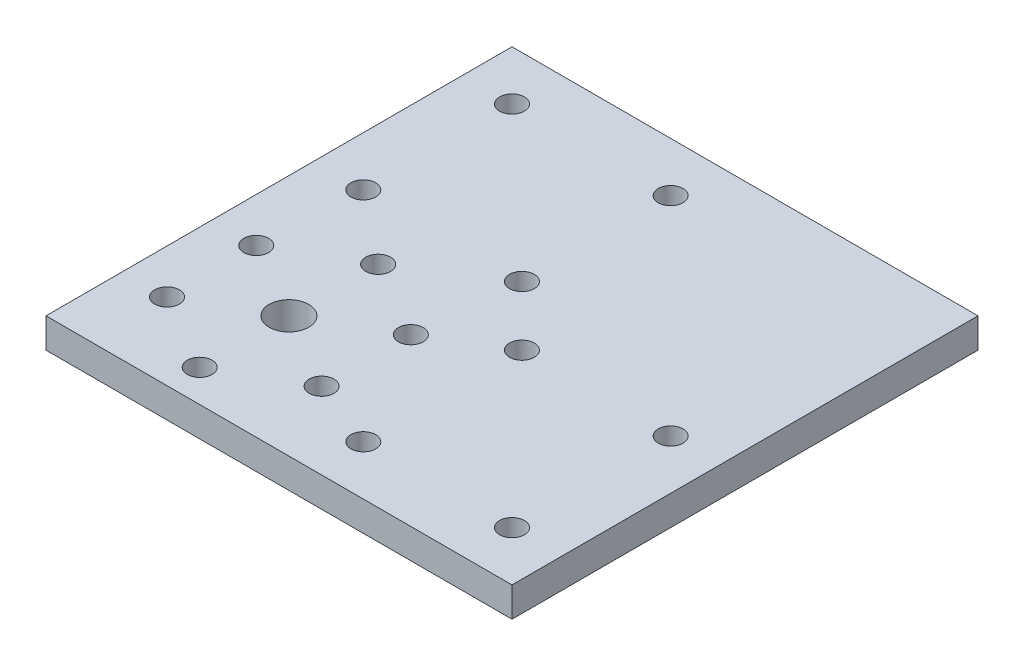
SolidWorks part; units mm, degrees
ref_plane "Front Plane" through (0, 0, 0) normal (0, 0, 1) x (1, 0, 0)
ref_plane "Top Plane" through (0, 0, 0) normal (0, 1, 0) x (1, 0, 0)
ref_plane "Right Plane" through (0, 0, 0) normal (1, 0, 0) x (0, 0, -1)
sketch "Sketch1" plane through (0, 0, 0) normal (0, 1, 0) x (1, 0, 0)
  line L0 (8, -10.5) -> (14, -10.5) construction
  line L1 (8, -7.5) -> (-8, -7.5) construction
  line L2 (8, -7.5) -> (8, 7.5) construction
  line L3 (8, 7.5) -> (-8, 7.5) construction
  line L4 (-8, -7.5) -> (-8, 7.5) construction
  line L5 (8, -7.5) -> (-8, 7.5) construction
  line L6 (8, 7.5) -> (-8, -7.5) construction
  line L7 (29, -29.5) -> (14, -29.5) construction
  line L8 (29, -29.5) -> (29, -13.5) construction
  line L9 (29, -13.5) -> (14, -13.5) construction
  line L10 (14, -29.5) -> (14, -13.5) construction
  line L11 (29, -29.5) -> (14, -13.5) construction
  line L12 (29, -13.5) -> (14, -29.5) construction
  line L13 (-13, 12.5) -> (34, 12.5)
  line L14 (34, 12.5) -> (34, -34.5)
  line L15 (34, -34.5) -> (-13, -34.5)
  line L16 (-13, -34.5) -> (-13, 12.5)
  line L17 (11, -7.5) -> (11, -13.5) construction
  circle A0 centre (8, -7.5) radius 3 construction
  circle A1 centre (14, -13.5) radius 3 construction
  point P0 (0, 0)
  point P6 (21.5, -21.5)
  dimension "D3" = 6
  dimension "D1" = 15
  dimension "D2" = 16
  dimension "D5" = 5
  dimension "D6" = 5
  dimension "D7" = 5
  dimension "D8" = 5
extrude "Boss-Extrude1" add sketch "Sketch1" along normal blind 3
hole_wizard "Tap Drill for M3x0.5 Tap1" positions "Sketch2" profile "Sketch3" hole size "M3x0.5" standard "ANSI Metric" end condition through all
sketch "Sketch2" plane through (0, 3, 0) normal (0, 1, 0) x (1, 0, 0)
  point P0 (-8, 7.5)
  point P3 (8, 7.5)
  point P6 (8, -7.5)
  point P9 (-8, -7.5)
  point P12 (14, -13.5)
  point P15 (29, -13.5)
  point P18 (29, -29.5)
  point P21 (14, -29.5)
sketch "Sketch3" plane through (-8, 3, -7.5) normal (1, 0, 0) x (0, 0, 1)
  line L0 (0, 0) -> (0, 3)
  line L1 (0, 3) -> (1.25, 3)
  line L2 (1.25, 3) -> (1.25, 0)
  line L5 (1.25, 0) -> (0, 0)
  line L11 (0, -6.35) -> (0, 107.95) construction
  dimension "Thru Hole Dia." = 2.5
  dimension "Thru Hole Depth" = 3
sketch "Chube Mounting" plane through (0, 3, 0) normal (0, 1, 0) x (1, 0, 0)
  line L1 (11.5, -10) -> (-13, -10) construction
  line L2 (11.5, -10) -> (11.5, -34.5) construction
  line L3 (11.5, -34.5) -> (-13, -34.5) construction
  line L4 (-13, -10) -> (-13, -34.5) construction
  line L5 (11.5, -10) -> (-13, -34.5) construction
  line L6 (11.5, -34.5) -> (-13, -10) construction
  circle A0 centre (-0.75, -22.25) radius 9 construction
  point P0 (-0.75, -22.25)
  point P6 (-0.75, -13.25)
  point P10 (7.0442, -17.75)
  point P13 (7.0442, -26.75)
  point P14 (-0.75, -31.25)
  point P15 (-8.5442, -26.75)
  point P16 (-8.5442, -17.75)
  point P17 (-0.75, -22.25)
  dimension "D2" = 18
  dimension "D1" = 10
  dimension "D3" = 6
hole_wizard "Tap Drill for M3x0.5 Tap2" positions "Sketch5" profile "Sketch6" hole size "M3x0.5" standard "ANSI Metric" end condition through all
sketch "Sketch5" plane through (0, 3, 0) normal (0, 1, 0) x (1, 0, 0)
  point P0 (-0.75, -13.25)
  point P3 (-8.5442, -17.75)
  point P6 (-8.5442, -26.75)
  point P9 (-0.75, -31.25)
  point P12 (7.0442, -26.75)
  point P15 (7.0442, -17.75)
sketch "Sketch6" plane through (-0.75, 3, 13.25) normal (1, 0, 0) x (0, 0, 1)
  line L0 (0, 0) -> (0, 3)
  line L1 (0, 3) -> (1.25, 3)
  line L2 (1.25, 3) -> (1.25, 0)
  line L5 (1.25, 0) -> (0, 0)
  line L11 (0, -6.35) -> (0, 107.95) construction
  dimension "Thru Hole Dia." = 2.5
  dimension "Thru Hole Depth" = 3
hole_wizard "Ø4.0 (4) Diameter Hole1" positions "Sketch7" profile "Sketch8" hole size "Ø4.0" standard "ANSI Metric" end condition through all
sketch "Sketch7" plane through (0, 3, 0) normal (0, 1, 0) x (1, 0, 0)
  point P0 (-0.75, -22.25)
sketch "Sketch8" plane through (-0.75, 3, 22.25) normal (1, 0, 0) x (0, 0, 1)
  line L0 (0, 0) -> (0, 3)
  line L1 (0, 3) -> (2, 3)
  line L2 (2, 3) -> (2, 0)
  line L5 (2, 0) -> (0, 0)
  line L11 (0, -6.35) -> (0, 107.95) construction
  dimension "Thru Hole Dia." = 4
  dimension "Thru Hole Depth" = 3
